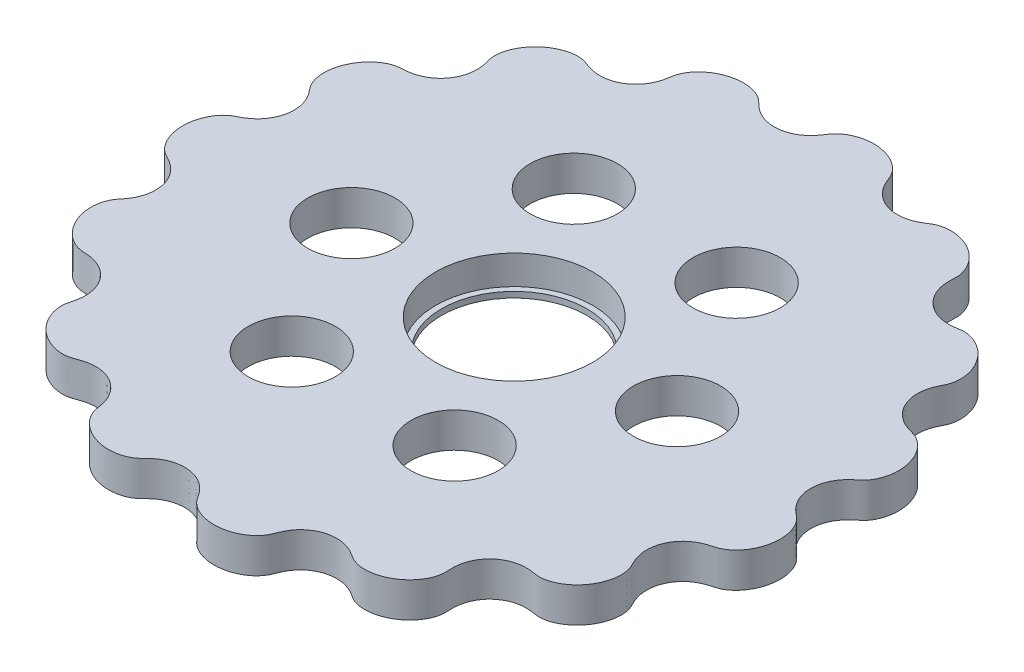
SolidWorks part; units mm, degrees
material "ABS PC"
ref_plane "前视基准面" through (0, 0, 0) normal (0, 0, 1) x (1, 0, 0)
ref_plane "上视基准面" through (0, 0, 0) normal (0, 1, 0) x (1, 0, 0)
ref_plane "右视基准面" through (0, 0, 0) normal (1, 0, 0) x (0, 0, -1)
sketch "草图3" plane through (0, 0, 0) normal (0, 1, 0) x (1, 0, 0)
  circle A0 centre (0, 0) radius 13.5
  circle A1 centre (0, 0) radius 28 construction
  circle A2 centre (-28, 0) radius 7.5
  arc A7 (51.1029, 1.1255) -> (51, 0) centre (57.2058, 0) ccw construction
  circle A14 centre (-14, 24.2487) radius 7.5
  circle A15 centre (14, 24.2487) radius 7.5
  circle A16 centre (28, 0) radius 7.5
  circle A17 centre (14, -24.2487) radius 7.5
  circle A18 centre (-14, -24.2487) radius 7.5
  spline S0 degree 4 number of poles 639 (46.5379, 25.7372) -> (46.2252, -24.7497) construction
  spline S1 degree 4 number of poles 546 (51, 0) -> (51.1029, 1.1255) construction
  spline S2 degree 4 number of poles 565 (51.0116, -0.3791) -> (51.0116, -0.3791)
  dimension "D1" = 27
  dimension "D2" = 56
  dimension "D3" = 15
  dimension "D6" = 28
  dimension "D4" = 6
extrude "凸台-拉伸1" add sketch "草图3" along normal blind 6
sketch "草图4" plane through (0, 0, 0) normal (0, -1, 0) x (1, 0, 0)
  circle A0 centre (0, 0) radius 13.5 construction
  circle A1 centre (0, 0) radius 13.5
  circle A2 centre (0, 0) radius 12.5
  dimension "D1" = 25
extrude "凸台-拉伸2" add sketch "草图4" against normal blind 1
